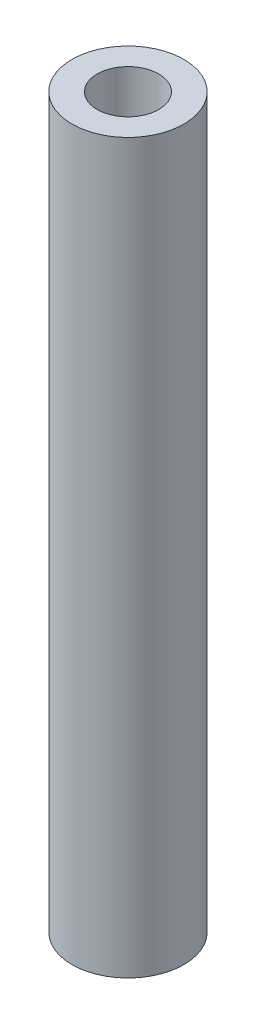
SolidWorks part; units mm, degrees
ref_plane "前视基准面" through (0, 0, 0) normal (0, 0, 1) x (1, 0, 0)
ref_plane "上视基准面" through (0, 0, 0) normal (0, 1, 0) x (1, 0, 0)
ref_plane "右视基准面" through (0, 0, 0) normal (1, 0, 0) x (0, 0, -1)
sketch "草图1" plane through (0, 0, 0) normal (0, 1, 0) x (1, 0, 0)
  circle A0 centre (0, 0) radius 1.65
  circle A1 centre (0, 0) radius 3
  dimension "D1" = 3.3
  dimension "D2" = 6
extrude "凸台-拉伸1" add sketch "草图1" along normal blind 39
